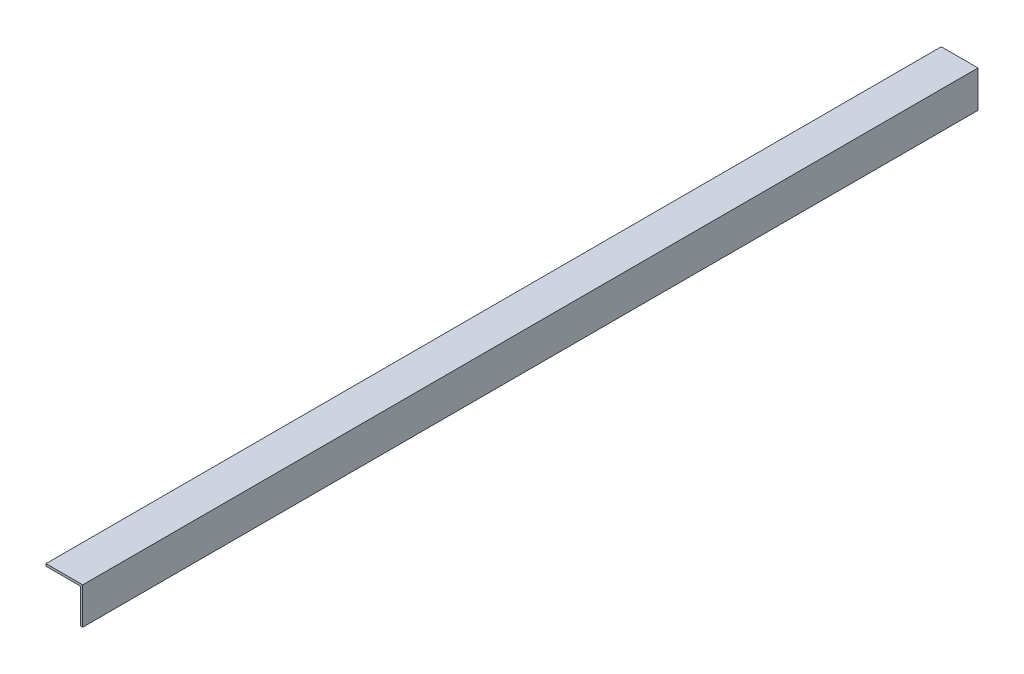
SolidWorks part; units mm, degrees
ref_plane "Front Plane" through (0, 0, 0) normal (0, 0, 1) x (1, 0, 0)
ref_plane "Top Plane" through (0, 0, 0) normal (0, 1, 0) x (1, 0, 0)
ref_plane "Right Plane" through (0, 0, 0) normal (1, 0, 0) x (0, 0, -1)
other "Configuration Table"
sketch "Sketch1" plane through (0, 0, 0) normal (0, 0, 1) x (1, 0, 0)
  line L0 (662, 1122) -> (660, 1122)
  line L1 (660, 1122) -> (660, 1152)
  line L2 (660, 1152) -> (630, 1152)
  line L3 (630, 1152) -> (630, 1154)
  line L4 (630, 1154) -> (662, 1154)
  line L5 (662, 1154) -> (662, 1122)
extrude "PRESS_uc_rafi_kosebent_sag_1" add sketch "Sketch1" against normal blind 780 from offset 20 separate body
